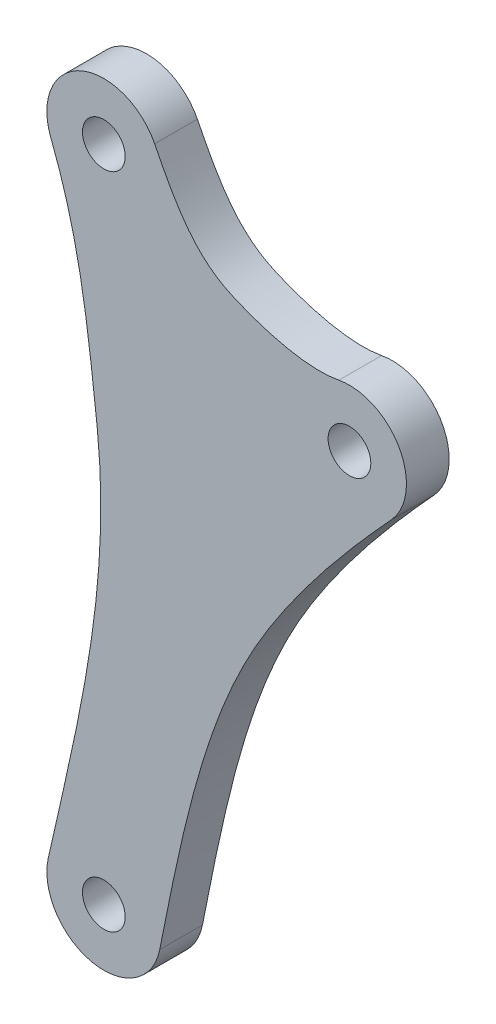
SolidWorks part; units mm, degrees
ref_plane "Plan de face" through (0, 0, 0) normal (0, 0, 1) x (1, 0, 0)
ref_plane "Plan de dessus" through (0, 0, 0) normal (0, 1, 0) x (1, 0, 0)
ref_plane "Plan de droite" through (0, 0, 0) normal (1, 0, 0) x (0, 0, -1)
sketch "Esquisse15" plane through (0, 0, 0) normal (0, 0, 1) x (1, 0, 0)
  circle A0 centre (81.0475, 75.4068) radius 1.5
  circle A1 centre (98.293, 65.3775) radius 1.5
  circle A2 centre (81.0475, 29.1742) radius 1.5
  arc A3 (84.6156, 77.2148) -> (77.3245, 73.9442) centre (81.0475, 75.4068) ccw
  arc A4 (77.1457, 30.0552) -> (84.9713, 28.3973) centre (81.0475, 29.1742) ccw
  arc A5 (101.2389, 62.6716) -> (97.5466, 69.3073) centre (98.293, 65.3775) ccw
  spline S0 degree 3 poles (77.1457, 30.0552) (79.0803, 38.6227) (81.6633, 48.7861) (79.931, 63.6887) (79.1436, 69.3138) (77.3245, 73.9442) knots 0 0 0 0 0.576573 0.676573 1 1 1 1
  spline S1 degree 3 poles (84.6156, 77.2148) (85.7656, 74.9453) (87.2845, 71.8967) (92.7096, 69.5389) (95.6927, 68.9552) (97.5466, 69.3073) knots 0 0 0 0 0.4561 0.5561 1 1 1 1
  spline S2 degree 3 poles (101.2389, 62.6716) (98.3763, 59.5552) (94.8996, 55.416) (88.2273, 44.7175) (86.5286, 36.2634) (84.9713, 28.3973) knots 0 0 0 0 0.311641 0.411641 1 1 1 1
  dimension "D1" = 3
  dimension "D2" = 3
  dimension "D3" = 3
  dimension "D4" = 8
  dimension "D5" = 8
  dimension "D6" = 8
extrude "Boss.-Extru.15" add sketch "Esquisse15" along normal blind 3 separate body
